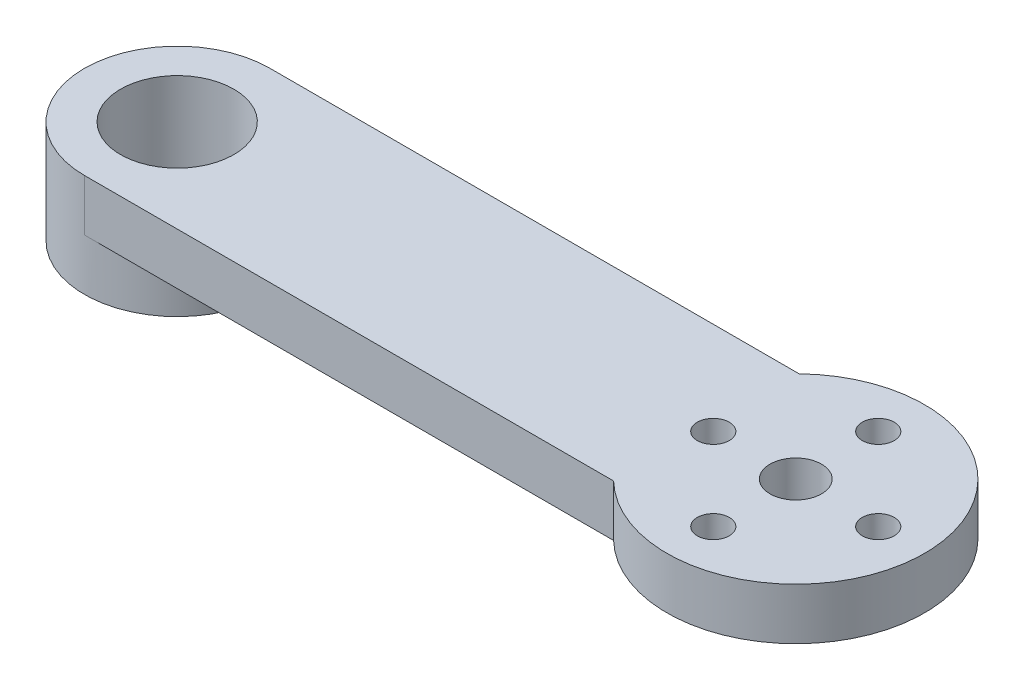
SolidWorks part; units mm, degrees
ref_plane "Front Plane" through (0, 0, 0) normal (0, 0, 1) x (1, 0, 0)
ref_plane "Top Plane" through (0, 0, 0) normal (0, 1, 0) x (1, 0, 0)
ref_plane "Right Plane" through (0, 0, 0) normal (1, 0, 0) x (0, 0, -1)
sketch "Sketch1" plane through (0, 0, 0) normal (0, 1, 0) x (1, 0, 0)
  line L0 (0, 9) -> (51.3253, 9)
  line L1 (0, -9) -> (51.3253, -9)
  arc A0 (0, 9) -> (0, -9) centre (0, 0) ccw
  arc A1 (51.3253, -9) -> (51.3253, 9) centre (60, 0) ccw
  dimension "D1" = 18
  dimension "D2" = 25
  dimension "D3" = 9
  dimension "D4" = 60
extrude "Boss-Extrude1" add sketch "Sketch1" along normal blind 5
sketch "Sketch2" plane through (0, 5, 0) normal (0, 1, 0) x (1, 0, 0)
  circle A1 centre (60, 0) radius 2.5
  dimension "D2" = 5
extrude "Cut-Extrude1" cut sketch "Sketch2" against normal through all
sketch "Sketch7" plane through (0, 0, 0) normal (0, -1, 0) x (1, 0, 0)
  circle A0 centre (0, 0) radius 9
  dimension "D1" = 18
extrude "Boss-Extrude3" add sketch "Sketch7" along normal blind 5
sketch "Sketch8" plane through (0, -5, 0) normal (0, -1, 0) x (1, 0, 0)
  circle A0 centre (0, 0) radius 5.5
  dimension "D1" = 11
extrude "Cut-Extrude3" cut sketch "Sketch8" against normal through all
sketch "Sketch9" plane through (0, 0, 0) normal (0, -1, 0) x (1, 0, 0)
  line L0 (60, 0) -> (60, 2.5) construction
  line L1 (60, 0) -> (62.5, 0) construction
  circle A0 centre (60, 8) radius 1.55
  circle A1 centre (60, -8) radius 1.55
  circle A2 centre (68, 0) radius 1.55
  circle A3 centre (52, 0) radius 1.55
  point P11 (0, 0)
  point P12 (0, 0)
  point P15 (0, 0)
  point P17 (0, 0)
  dimension "D1" = 3.1
  dimension "D2" = 8
  dimension "D3" = 8
  dimension "D4" = 8
  dimension "D5" = 8
extrude "Cut-Extrude4" cut sketch "Sketch9" against normal through all
